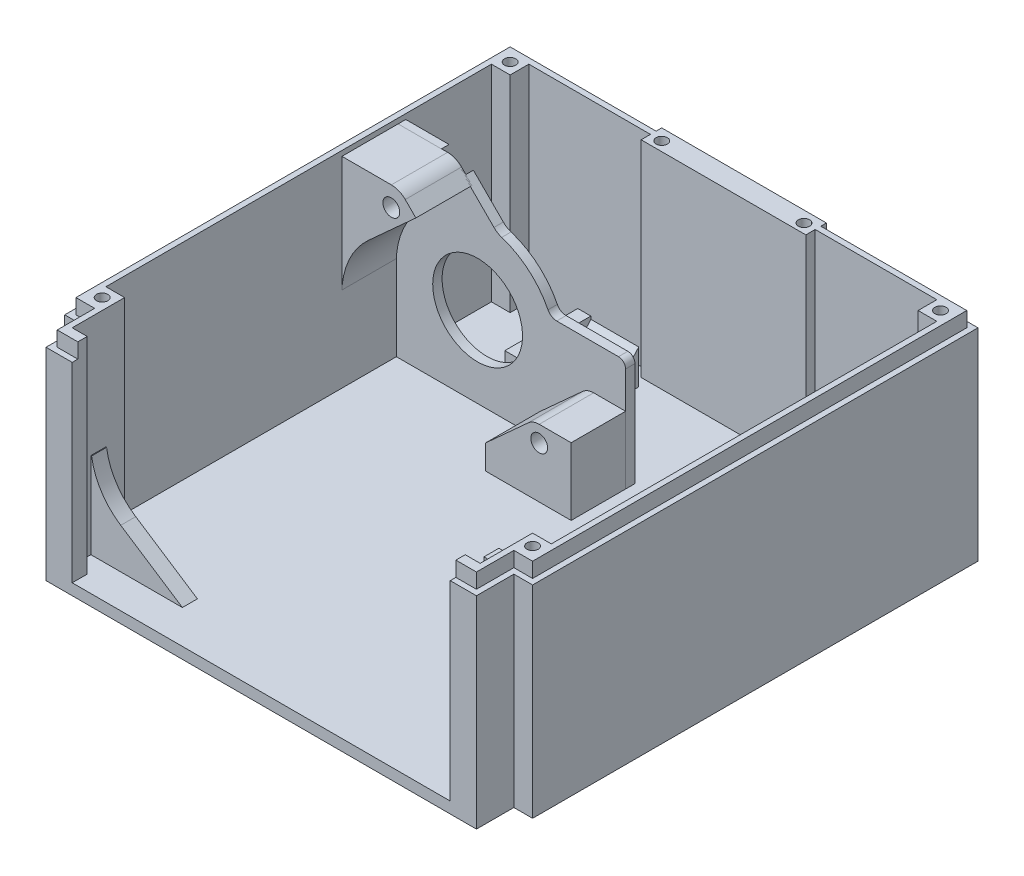
SolidWorks part; units mm, degrees
material "ABS"
ref_plane "Front Plane" through (0, 0, 0) normal (0, 0, 1) x (1, 0, 0)
ref_plane "Top Plane" through (0, 0, 0) normal (0, 1, 0) x (1, 0, 0)
ref_plane "Right Plane" through (0, 0, 0) normal (1, 0, 0) x (0, 0, -1)
sketch "Sketch1" plane through (0, 0, 0) normal (0, 1, 0) x (1, 0, 0)
  line L1 (-62.5, -64.5) -> (62.5, -64.5)
  line L2 (-62.5, -64.5) -> (-62.5, 64.5)
  line L3 (-62.5, 64.5) -> (62.5, 64.5)
  line L4 (62.5, -64.5) -> (62.5, 64.5)
  line L5 (-62.5, -64.5) -> (62.5, 64.5) construction
  line L6 (-62.5, 64.5) -> (62.5, -64.5) construction
  line L7 (-62.5, -54.5) -> (-57.5, -54.5)
  line L8 (-62.5, -54.5) -> (-62.5, -64.5)
  line L9 (-62.5, -64.5) -> (-57.5, -64.5)
  line L10 (-57.5, -54.5) -> (-57.5, -64.5)
  line L11 (62.5, -54.5) -> (57.5, -54.5)
  line L12 (62.5, -54.5) -> (62.5, -64.5)
  line L13 (62.5, -64.5) -> (57.5, -64.5)
  line L14 (57.5, -54.5) -> (57.5, -64.5)
  point P0 (0, 0)
  dimension "D1" = 129
  dimension "D2" = 125
  dimension "D3" = 10
  dimension "D4" = 5
  dimension "D5" = 10
  dimension "D6" = 5
extrude "Boss-Extrude1" add sketch "Sketch1" along normal blind 3 contours L14 L11 L4 L3 L2 L7 L10 L1
sketch "Sketch2" plane through (0, 3, 0) normal (0, 1, 0) x (1, 0, 0)
  line L0 (-59.5, 61.5) -> (59.5, 61.5)
  line L1 (-59.5, 61.5) -> (-59.5, -51.5)
  line L2 (-59.5, -51.5) -> (-54.5, -51.5)
  line L3 (-54.5, -51.5) -> (-54.5, -58.5)
  line L4 (-54.5, -58.5) -> (54.5, -58.5)
  line L5 (54.5, -58.5) -> (54.5, -51.5)
  line L6 (54.5, -51.5) -> (59.5, -51.5)
  line L7 (59.5, -51.5) -> (59.5, 61.5)
  line L8 (57.5, -64.5) -> (57.5, -54.5)
  line L9 (57.5, -54.5) -> (62.5, -54.5)
  line L10 (62.5, -54.5) -> (62.5, 64.5)
  line L11 (62.5, 64.5) -> (-62.5, 64.5)
  line L12 (-62.5, 64.5) -> (-62.5, -54.5)
  line L13 (-62.5, -54.5) -> (-57.5, -54.5)
  line L14 (-57.5, -54.5) -> (-57.5, -64.5)
  line L15 (-57.5, -64.5) -> (57.5, -64.5)
  line L16 (57.5, -64.5) -> (57.5, -54.5)
  line L17 (57.5, -54.5) -> (62.5, -54.5)
  line L18 (62.5, -54.5) -> (62.5, 64.5)
  line L19 (62.5, 64.5) -> (-62.5, 64.5)
  line L20 (-62.5, 64.5) -> (-62.5, -54.5)
  line L21 (-62.5, -54.5) -> (-57.5, -54.5)
  line L22 (-57.5, -54.5) -> (-57.5, -64.5)
  line L23 (-57.5, -64.5) -> (57.5, -64.5)
  line L24 (0, 95.4757) -> (0, 21.0279) construction
  line L25 (-59.5, 61.5) -> (-54.5, 61.5)
  line L26 (-59.5, 61.5) -> (-59.5, 56.5)
  line L27 (-59.5, 56.5) -> (-54.5, 56.5)
  line L28 (-54.5, 61.5) -> (-54.5, 56.5)
  line L29 (59.5, 56.5) -> (54.5, 56.5)
  line L30 (54.5, 61.5) -> (54.5, 56.5)
  line L31 (59.5, 61.5) -> (54.5, 61.5)
  line L32 (59.5, 61.5) -> (59.5, 56.5)
  line L34 (-54.5, -51.5) -> (-59.5, -51.5)
  line L35 (-54.5, -51.5) -> (-54.5, -46.5)
  line L36 (-54.5, -46.5) -> (-59.5, -46.5)
  line L37 (-59.5, -51.5) -> (-59.5, -46.5)
  line L38 (54.5, -51.5) -> (59.5, -51.5)
  line L39 (54.5, -51.5) -> (54.5, -46.5)
  line L40 (54.5, -46.5) -> (59.5, -46.5)
  line L41 (59.5, -51.5) -> (59.5, -46.5)
  line L42 (22, 61.5) -> (-22, 61.5)
  line L43 (22, 61.5) -> (22, 59)
  line L44 (22, 59) -> (-22, 59)
  line L45 (-22, 61.5) -> (-22, 59)
  circle A0 centre (-57.5, 59.5) radius 1.5
  circle A1 centre (57.5, 59.5) radius 1.5
  circle A2 centre (-57.5, -49.5) radius 1.5
  circle A3 centre (57.5, -49.5) radius 1.5
  circle A4 centre (-19, 61.5) radius 1.5
  circle A5 centre (19, 61.5) radius 1.5
  point P40 (0, 59)
  dimension "D12" = 3
  dimension "D19" = 3
  dimension "D20" = 3
  dimension "D27" = 3
  dimension "D28" = 3
  dimension "D2" = 3
  dimension "D3" = 3
  dimension "D4" = 3
  dimension "D5" = 3
  dimension "D6" = 3
  dimension "D7" = 6
  dimension "D8" = 3
  dimension "D9" = 3
  dimension "D10" = 5
  dimension "D11" = 5
  dimension "D13" = 3
  dimension "D14" = 3
  dimension "D15" = 5
  dimension "D16" = 5
  dimension "D17" = 3
  dimension "D18" = 3
  dimension "D21" = 3
  dimension "D22" = 3
  dimension "D23" = 2.5
  dimension "D24" = 22
  dimension "D25" = 3
  dimension "D26" = 3
  dimension "D1" = 0
extrude "Boss-Extrude2" add sketch "Sketch2" along normal blind 55
sketch "Sketch14" plane through (0, 0, -31.119) normal (0, 0, -1) x (-1, 0, 0)
  line L0 (-1.7313, 24.25) -> (-1.7313, 3)
  line L1 (54.5, 3) -> (22, 3) construction
  line L2 (51.5558, 41.4884) -> (51.5558, 51.3861)
  line L3 (42.5935, 55.0985) -> (33.4381, 45.943)
  line L4 (51.5558, 41.4884) -> (51.5558, 51.3861)
  line L5 (42.5935, 55.0985) -> (33.4381, 45.943)
  line L6 (58.8568, 24.6361) -> (58.8568, 3)
  line L7 (-1.7313, 3) -> (58.8568, 3)
  line L8 (-1.7313, 30.7722) -> (-1.7313, 24.25)
  line L9 (0.1697, 22.349) -> (6.8497, 22.349)
  line L10 (10.614, 20.8948) -> (23.6529, 9.0528)
  line L11 (16.6825, 32.6732) -> (0.1697, 32.6732)
  line L12 (-1.7313, 30.7722) -> (-1.7313, 24.25)
  line L13 (0.1697, 22.349) -> (6.8497, 22.349)
  line L14 (10.614, 20.8948) -> (23.6529, 9.0528)
  line L15 (16.6825, 32.6732) -> (0.1697, 32.6732)
  line L16 (46.3058, 56.6362) -> (59.9736, 56.6362)
  line L17 (-1.6185, 22.2795) -> (2.0476, 14.4174)
  line L18 (10.5181, 12.9238) -> (10.8691, 13.2747)
  line L19 (11.5762, 13.5676) -> (16.8614, 13.5676)
  line L20 (18.205, 13.0492) -> (10.1644, 20.3401)
  line L21 (6.8059, 21.6361) -> (0.0557, 21.6361)
  line L22 (-1.5958, 23.5453) -> (2.0476, 14.4174)
  line L23 (10.5181, 12.9238) -> (10.8691, 13.2747)
  line L24 (11.5762, 13.5676) -> (16.8614, 13.5676)
  line L27 (58.8568, 3) -> (59.9736, 3)
  line L28 (58.8568, 3) -> (58.8568, 24.6361)
  line L29 (58.8568, 24.6361) -> (59.9736, 24.6361)
  line L30 (59.9736, 3) -> (59.9736, 24.6361)
  line L31 (59.9736, 56.6362) -> (59.9736, 24.6361)
  arc A0 (16.8614, 13.5676) -> (20.0293, 12.3438) centre (16.8614, 8.8557) cw
  arc A1 (2.0476, 14.4174) -> (10.5181, 12.9238) centre (6.8058, 16.6361) ccw
  arc A2 (51.5558, 41.4884) -> (33.4381, 45.943) centre (37.8058, 24.6361) ccw
  arc A3 (51.5558, 51.3861) -> (42.5935, 55.0985) centre (46.3058, 51.3861) ccw
  arc A5 (51.5558, 51.3861) -> (42.5935, 55.0985) centre (46.3058, 51.3861) ccw
  arc A6 (2.0476, 14.4174) -> (10.5181, 12.9238) centre (6.8058, 16.6361) ccw
  arc A7 (33.4381, 45.943) -> (31.3659, 44.6779) centre (29.7858, 49.5953) cw
  arc A8 (51.5558, 41.4884) -> (52.2034, 39.9936) centre (53.6048, 41.4884) ccw
  arc A9 (-1.7313, 24.25) -> (0.1697, 22.349) centre (0.1697, 24.25) ccw
  arc A10 (10.614, 20.8948) -> (6.8497, 22.349) centre (6.8497, 16.75) ccw
  arc A11 (23.6529, 9.0528) -> (19.0038, 34.1034) centre (37.8058, 24.6361) ccw
  arc A12 (16.6825, 32.6732) -> (19.0038, 34.1034) centre (16.6825, 35.2722) ccw
  arc A13 (0.1697, 32.6732) -> (-1.7313, 30.7722) centre (0.1697, 30.7722) ccw
  arc A14 (-1.7313, 24.25) -> (0.1697, 22.349) centre (0.1697, 24.25) ccw
  arc A15 (10.614, 20.8948) -> (6.8497, 22.349) centre (6.8497, 16.75) ccw
  arc A16 (23.6529, 9.0528) -> (19.0038, 34.1034) centre (37.8058, 24.6361) ccw
  arc A17 (16.6825, 32.6732) -> (19.0038, 34.1034) centre (16.6825, 35.2722) ccw
  arc A18 (0.1697, 32.6732) -> (-1.7313, 30.7722) centre (0.1697, 30.7722) ccw
  arc A19 (44.0589, 51.5039) -> (48.5527, 51.2684) centre (46.3058, 51.3861) ccw construction
  arc A20 (44.0589, 51.5039) -> (48.5527, 51.2684) centre (46.3058, 51.3861) ccw
  arc A21 (48.5527, 51.2684) -> (44.0589, 51.5039) centre (46.3058, 51.3861) ccw construction
  arc A22 (48.5527, 51.2684) -> (44.0589, 51.5039) centre (46.3058, 51.3861) ccw
  arc A23 (4.5589, 16.7539) -> (9.0527, 16.5184) centre (6.8058, 16.6361) ccw construction
  arc A24 (9.0527, 16.5184) -> (4.5589, 16.7539) centre (6.8058, 16.6361) ccw construction
  arc A25 (4.5589, 16.7539) -> (9.0527, 16.5184) centre (6.8058, 16.6361) ccw
  arc A26 (9.0527, 16.5184) -> (4.5589, 16.7539) centre (6.8058, 16.6361) ccw
  circle A27 centre (37.8058, 24.6361) radius 12
  ellipse E4 centre (11.5764, 12.5676) end of major axis (10.6988, 13.0474) minor radius 1 (11.5762, 13.5676) -> (10.8691, 13.2747) ccw
  ellipse E5 centre (16.8611, 11.5675) end of major axis (18.6261, 12.509) minor radius 2 (18.205, 13.0492) -> (16.8614, 13.5676) ccw
  ellipse E6 centre (6.8057, 16.6359) end of major axis (8.6058, 21.3009) minor radius 5 (10.1644, 20.3401) -> (6.8059, 21.6361) ccw
  ellipse E7 centre (0.0559, 24.1362) end of major axis (-1.712, 22.3683) minor radius 2.5 (-1.6185, 22.2795) -> (0.0557, 21.6361) ccw
  ellipse E8 centre (11.5764, 12.5676) end of major axis (10.6988, 13.0474) minor radius 1 (11.5762, 13.5676) -> (10.8691, 13.2747) ccw
  dimension "D4" = 24
  dimension "D1" = 0
  dimension "D2" = 0
  dimension "D3" = 0
extrude "Boss-Extrude10" add sketch "Sketch14" along normal blind 2.5 separate body contours L15 A18 L12 A14 L13 A15 L14 A16 A17 | E8 L24 A0 L14 A15 L13 A14 L22 A6 L23 A26 A25 | A16 A8 L4 A5 L5 A7 A22 A20 | L24 E8 L23 A6 L22 A14 L0 L7 L6 A16 L14 A0 | L27 L30 L29 L6 | A16 L29 L31 L16 A5 L4 A8
sketch "Sketch21" plane through (0, 0, -16.569) normal (0, 0, -1) x (-1, 0, 0)
  line L0 (59.9736, 56.6362) -> (46.3058, 56.6362)
  line L1 (59.9736, 56.6362) -> (59.9736, 24.6361)
  line L2 (51.5558, 41.4884) -> (51.5558, 51.3861)
  line L3 (42.5935, 55.0985) -> (33.4381, 45.943)
  line L5 (42.5935, 55.0985) -> (33.4381, 45.943)
  line L6 (59.9736, 56.6362) -> (59.9736, 3) construction
  line L7 (59.9736, 24.6361) -> (59.5558, 24.6361)
  line L8 (-1.7313, 3) -> (-1.7313, 20.9902)
  line L9 (-1.7313, 30.7722) -> (-1.7313, 3) construction
  line L10 (-1.7313, 20.9902) -> (8.4879, 20.9902)
  line L11 (8.4879, 20.9902) -> (21.1422, 9.4976)
  line L12 (21.1422, 9.4976) -> (21.1422, 3)
  line L13 (-1.7313, 3) -> (59.9736, 3) construction
  line L14 (10.2113, 20.4513) -> (23.2502, 8.6093) construction
  line L15 (-1.7313, 3) -> (21.1422, 3)
  line L16 (52.4286, 40.7369) -> (39.7483, 52.2533)
  circle A0 centre (37.8058, 24.6361) radius 21.75
  arc A1 (9.7331, 19.8593) -> (6.8058, 20.9902) centre (6.8058, 16.6361) ccw
  arc A2 (51.5558, 41.4884) -> (33.4381, 45.943) centre (37.8058, 24.6361) ccw
  arc A3 (51.5558, 51.3861) -> (42.5935, 55.0985) centre (46.3058, 51.3861) ccw
  arc A4 (51.5558, 41.4884) -> (33.4381, 45.943) centre (37.8058, 24.6361) ccw
  arc A5 (51.5558, 51.3861) -> (42.5935, 55.0985) centre (46.3058, 51.3861) ccw
  circle A6 centre (6.8058, 16.6361) radius 2.25 construction
  circle A7 centre (6.8058, 16.6361) radius 2.25
  circle A9 centre (46.3058, 51.3861) radius 2.25
  arc M5 (33.4381, 45.943) -> (51.5558, 41.4884) centre (37.8058, 24.6361) cw
  line M6 (51.5558, 41.4884) -> (51.5558, 51.3861)
  arc M7 (51.5558, 51.3861) -> (42.5935, 55.0985) centre (46.3058, 51.3861) ccw
  line M8 (42.5935, 55.0985) -> (33.4381, 45.943)
  arc M9 (49.7111, 51.2076) -> (42.9005, 51.5646) centre (46.3058, 51.3861) cw
  arc M10 (42.9005, 51.5646) -> (49.7111, 51.2076) centre (46.3058, 51.3861) cw
  dimension "D1" = 0
extrude "Boss-Extrude11" add sketch "Sketch21" along normal blind 15 separate body contours A0 L7 L1 L0 M7 M6 | M8 M5 M6 M7 M10 M9 | L11 A1 L10 L8 L15 L12 | A9 M9 M10
sketch "Sketch22" plane through (0, 58, 0) normal (0, 1, 0) x (1, 0, 0)
  line L0 (62.5, 64.5) -> (22, 64.5)
  line L1 (62.5, 64.5) -> (-62.5, 64.5) construction
  line L4 (-22, 64.5) -> (-62.5, 64.5)
  line L5 (22, 61.5) -> (22, 59) construction
  line L6 (-22, 61.5) -> (-22, 59) construction
  line L8 (-57.5, -64.5) -> (57.5, -64.5)
  line L9 (57.5, -64.5) -> (57.5, -54.5)
  line L10 (57.5, -54.5) -> (62.5, -54.5)
  line L11 (62.5, -54.5) -> (62.5, 64.5)
  line L12 (62.5, 64.5) -> (-62.5, 64.5)
  line L13 (-62.5, 64.5) -> (-62.5, -54.5)
  line L14 (-62.5, -54.5) -> (-57.5, -54.5)
  line L15 (-57.5, -54.5) -> (-57.5, -64.5)
  line L16 (-57.5, -64.5) -> (57.5, -64.5)
  line L17 (57.5, -64.5) -> (57.5, -54.5)
  line L18 (57.5, -54.5) -> (62.5, -54.5)
  line L19 (62.5, -54.5) -> (62.5, 64.5)
  line L21 (-62.5, 64.5) -> (-62.5, -54.5)
  line L22 (-62.5, -54.5) -> (-57.5, -54.5)
  line L23 (-57.5, -54.5) -> (-57.5, -64.5)
  dimension "D1" = 0
extrude "Cut-Extrude-Thin2" cut sketch "Sketch22" against normal blind 4 and the other way through all thin thin type one direction reverse wall 1.5
surface "Surface-Offset1" parameters "D1"=0
sketch "Sketch23" plane through (0, 3, 0) normal (0, 1, 0) x (1, 0, 0)
  line L0 (0, 65.3767) -> (0, 34.5683) construction
  line L5 (20.1448, 56.5) -> (20.1448, 37)
  line L6 (32.9297, 37) -> (20.1448, 37)
  line L7 (32.9297, 56.5) -> (32.9297, 37)
  line L8 (32.9297, 56.5) -> (20.1448, 56.5)
  line L10 (-32.9297, 56.5) -> (-20.1448, 56.5)
  line L11 (-32.9297, 56.5) -> (-32.9297, 37)
  line L12 (-32.9297, 37) -> (-20.1448, 37)
  line L13 (-20.1448, 56.5) -> (-20.1448, 37)
  line L14 (-32.9297, 59.0019) -> (-32.9297, 34.9481) construction
extrude "Boss-Extrude15" add sketch "Sketch23" along normal up to surface (9.2444 mm away)
sketch "Sketch28" plane through (0, 3, 0) normal (0, 1, 0) x (1, 0, 0)
  line L0 (-32.9297, 37) -> (-20.1448, 37) construction
  line L1 (-32.9297, 56.5) -> (-36.4297, 56.5)
  line L2 (-32.9297, 56.5) -> (-32.9297, 37)
  line L3 (-32.9297, 37) -> (-36.4297, 37)
  line L4 (-36.4297, 56.5) -> (-36.4297, 37)
  line L6 (32.9297, 56.5) -> (36.4297, 56.5)
  line L7 (32.9297, 56.5) -> (32.9297, 37)
  line L8 (32.9297, 37) -> (36.4297, 37)
  line L9 (36.4297, 56.5) -> (36.4297, 37)
  dimension "D1" = 3.5
  dimension "D2" = 3.5
extrude "Boss-Extrude16" add sketch "Sketch28" along normal blind 10
sketch "Sketch29" plane through (0, 0, -37) normal (0, 0, 1) x (1, 0, 0)
  line L1 (-29.8007, 3.0145) -> (-23.8007, 3.0145)
  line L2 (-29.8007, 3.0145) -> (-29.8007, 5.5145)
  line L3 (-29.8007, 5.5145) -> (-23.8007, 5.5145)
  line L4 (-23.8007, 3.0145) -> (-23.8007, 5.5145)
  line L5 (23.9025, 3.0145) -> (29.9025, 3.0145)
  line L6 (23.9025, 3.0145) -> (23.9025, 5.5145)
  line L7 (23.9025, 5.5145) -> (29.9025, 5.5145)
  line L8 (29.9025, 3.0145) -> (29.9025, 5.5145)
  dimension "D1" = 6
  dimension "D2" = 2.5
  dimension "D3" = 6
extrude "Cut-Extrude9" cut sketch "Sketch29" against normal blind 21
sketch "Sketch31" plane through (0, 0, -33.619) normal (0, 0, -1) x (-1, 0, 0)
  circle A0 centre (6.8058, 16.6361) radius 2.25 construction
  circle A1 centre (6.8058, 16.6361) radius 2.25
  circle A2 centre (6.8058, 16.6361) radius 5.5
  circle A4 centre (46.3058, 51.3861) radius 5.5
  dimension "D1" = 11
  dimension "D2" = 11
extrude "Cut-Extrude10" cut sketch "Sketch31" against normal blind 2
sketch "Sketch35" plane through (0, 0, 55.5) normal (0, 0, -1) x (-1, 0, 0)
  line L1 (-54.5, 55) -> (-50.5, 55)
  line L2 (-54.5, 55) -> (-54.5, 3)
  line L3 (-54.5, 3) -> (-50.5, 3)
  line L4 (46.5389, 13.7798) -> (30.0583, 3)
  line L5 (30.0583, 3) -> (54.5, 3)
  line L6 (54.5, 3) -> (54.5, 25.9467)
  line L7 (54.5, 25.9467) -> (54.3117, 25.9329)
  line L8 (46.5389, 13.7798) -> (30.0583, 3)
  line L9 (30.0583, 3) -> (54.5, 3)
  line L10 (54.5, 3) -> (54.5, 25.9467)
  line L11 (54.5, 25.9467) -> (54.3117, 25.9329)
  line L12 (-50.5, 55) -> (-50.5, 3)
  arc A1 (46.5389, 13.7798) -> (54.3117, 25.9329) centre (36.9105, 28.5) ccw
  arc A2 (46.5389, 13.7798) -> (54.3117, 25.9329) centre (36.9105, 28.5) ccw
  dimension "D1" = 0
extrude "Boss-Extrude20" add sketch "Sketch35" along normal blind 4 separate body
sketch "Sketch36" plane through (0, 58, 0) normal (0, 1, 0) x (1, 0, 0)
  line L8 (-54.5, -60.5) -> (-50.5, -60.5)
  line L9 (-50.5, -60.5) -> (-50.5, -64.5)
  line L10 (-50.5, -64.5) -> (50.5, -64.5)
  line L11 (50.5, -64.5) -> (50.5, -60.5)
  line L12 (50.5, -60.5) -> (54.5, -60.5)
  line L13 (54.5, -60.5) -> (54.5, -55.5)
  line L14 (54.5, -55.5) -> (-54.5, -55.5)
  line L15 (-54.5, -55.5) -> (-54.5, -60.5)
  line L16 (-54.5, -60.5) -> (-50.5, -60.5)
  line L17 (-50.5, -60.5) -> (-50.5, -64.5)
  line L18 (-50.5, -64.5) -> (50.5, -64.5)
  line L19 (50.5, -64.5) -> (50.5, -60.5)
  line L20 (50.5, -60.5) -> (54.5, -60.5)
  line L21 (54.5, -60.5) -> (54.5, -55.5)
  line L22 (54.5, -55.5) -> (-54.5, -55.5)
  line L23 (-54.5, -55.5) -> (-54.5, -60.5)
  dimension "D1" = 0
extrude "Cut-Extrude18" cut sketch "Sketch36" against normal blind 55
